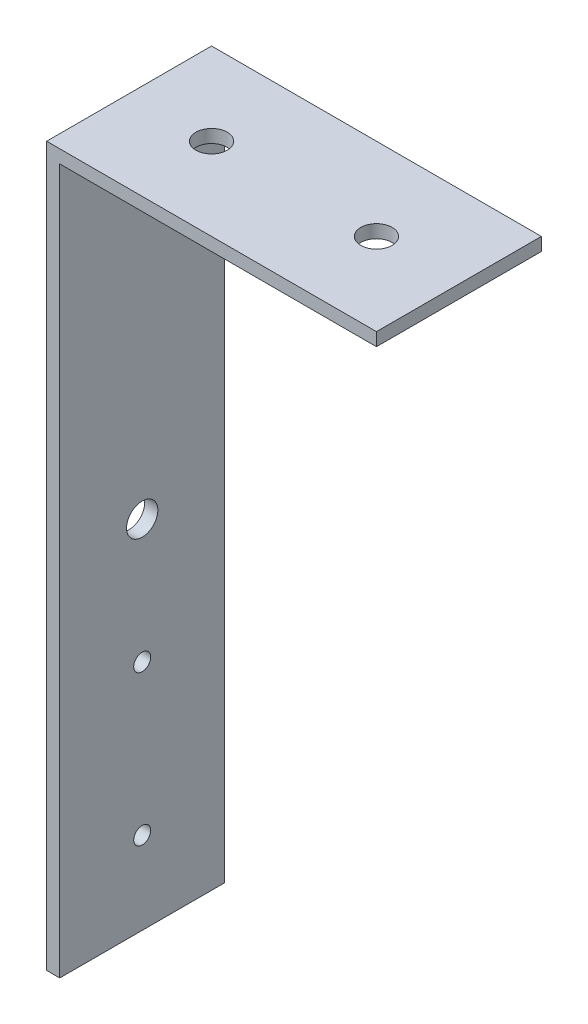
SolidWorks part; units mm, degrees
ref_plane "Front Plane" through (0, 0, 0) normal (0, 0, 1) x (1, 0, 0)
ref_plane "Top Plane" through (0, 0, 0) normal (0, 1, 0) x (1, 0, 0)
ref_plane "Right Plane" through (0, 0, 0) normal (1, 0, 0) x (0, 0, -1)
sketch "Sketch2" plane through (0, 0, 0) normal (0, 0, 1) x (1, 0, 0)
  line L0 (0, 0) -> (0, 87.1)
  line L1 (0, 87.1) -> (40, 87.1)
  line L2 (1.5875, 0) -> (1.5875, 85.5125)
  line L3 (1.5875, 85.5125) -> (40, 85.5125)
  line L4 (40, 87.1) -> (40, 85.5125)
  line L5 (0, 0) -> (1.5875, 0)
  dimension "D1" = 40
  dimension "D2" = 87.1
  dimension "D3" = 1.5875
extrude "Boss-Extrude1" add sketch "Sketch2" along normal blind 20
hole_wizard "#6 Clearance Hole1" positions "Sketch4" profile "Sketch3" hole size "#6" standard "ANSI Inch" end condition through all
sketch "Sketch4" plane through (0, 87.1, 0) normal (0, 1, 0) x (1, 0, 0)
  line L0 (40, 0) -> (0, 0) construction
  line L1 (0, -20) -> (0, 0) construction
  point P0 (10, -10)
  point P2 (30, -10)
  dimension "D1" = 10
  dimension "D2" = 10
  dimension "D3" = 20
sketch "Sketch3" plane through (10, 87.1, 10) normal (1, 0, 0) x (0, 0, 1)
  line L0 (0, 0) -> (0, 87.1)
  line L1 (0, 87.1) -> (1.8986, 87.1)
  line L2 (1.8986, 87.1) -> (1.8986, 0)
  line L5 (1.8986, 0) -> (0, 0)
  line L11 (0, -6.35) -> (0, 107.95) construction
  dimension "Thru Hole Dia." = 3.7973
  dimension "Thru Hole Depth" = 87.1
hole_wizard "#1 Clearance Hole2" positions "Sketch8" profile "Sketch7" hole size "#1" standard "ANSI Inch" end condition through all
sketch "Sketch8" plane through (0, 0, 0) normal (-1, 0, 0) x (0, 0, 1)
  line L0 (20, 0) -> (0, 0) construction
  line L1 (20, 87.1) -> (20, 0) construction
  point P0 (10, 10)
  point P2 (10, 28.2)
  dimension "D1" = 10
  dimension "D2" = 10
  dimension "D3" = 18.2
sketch "Sketch7" plane through (0, 10, 10) normal (0, 1, 0) x (0, 0, 1)
  line L0 (0, 0) -> (0, 40)
  line L1 (0, 40) -> (1.0287, 40)
  line L2 (1.0287, 40) -> (1.0287, 0)
  line L5 (1.0287, 0) -> (0, 0)
  line L11 (0, -6.35) -> (0, 107.95) construction
  dimension "Thru Hole Dia." = 2.0574
  dimension "Thru Hole Depth" = 40
hole_wizard "#6 Clearance Hole2" positions "Sketch10" profile "Sketch9" hole size "#6" standard "ANSI Inch" end condition through all
sketch "Sketch10" plane through (0, 0, 0) normal (-1, 0, 0) x (0, 0, 1)
  line L0 (0, 87.1) -> (0, 0) construction
  circle A0 centre (10, 28.2) radius 1.0287 construction
  point P0 (10, 43.2)
  dimension "D1" = 15
  dimension "D2" = 10
sketch "Sketch9" plane through (0, 43.2, 10) normal (0, 1, 0) x (0, 0, 1)
  line L0 (0, 0) -> (0, 40)
  line L1 (0, 40) -> (1.8986, 40)
  line L2 (1.8986, 40) -> (1.8986, 0)
  line L5 (1.8986, 0) -> (0, 0)
  line L11 (0, -6.35) -> (0, 107.95) construction
  dimension "Thru Hole Dia." = 3.7973
  dimension "Thru Hole Depth" = 40
